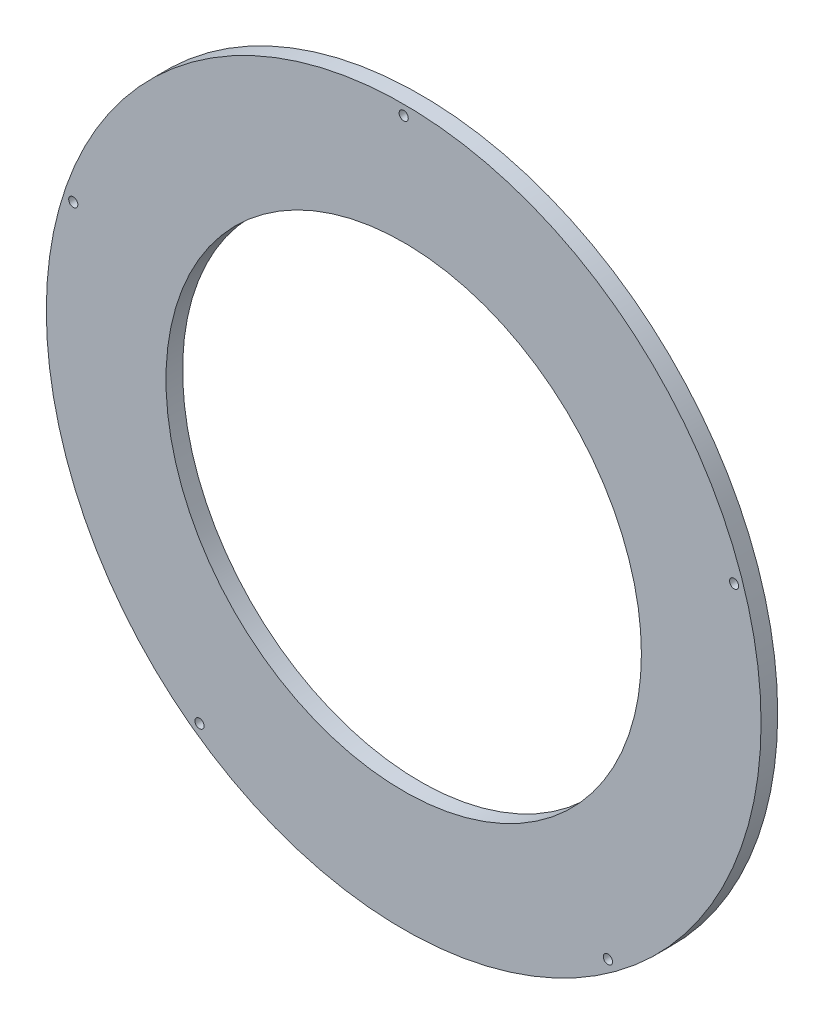
SolidWorks part; units mm, degrees
ref_plane "Front Plane" through (0, 0, 0) normal (0, 0, 1) x (1, 0, 0)
ref_plane "Top Plane" through (0, 0, 0) normal (0, 1, 0) x (1, 0, 0)
ref_plane "Right Plane" through (0, 0, 0) normal (1, 0, 0) x (0, 0, -1)
sketch "Sketch1" plane through (0, 0, 0) normal (0, 0, 1) x (1, 0, 0)
  circle A0 centre (0, 0) radius 215
  circle A1 centre (0, 0) radius 143
extrude "Plate" add sketch "Sketch1" along normal blind 10
sketch "Sketch2" plane through (0, 0, 0) normal (0, 0, 1) x (1, 0, 0)
  circle A0 centre (0, 0) radius 204
  circle A1 centre (0, 0) radius 144
extrude "Comb_groove" cut sketch "Sketch2" along normal blind 4
sketch "Sketch3" plane through (0, 0, 0) normal (0, 0, 1) x (1, 0, 0)
  circle A0 centre (198.7708, 64.5846) radius 2.75
  circle A1 centre (0, 209) radius 2.75
  circle A2 centre (-198.7708, 64.5846) radius 2.75
  circle A3 centre (-122.8471, -169.0846) radius 2.75
  circle A4 centre (122.8471, -169.0846) radius 2.75
extrude "Rod_holes" cut sketch "Sketch3" along normal blind 10
